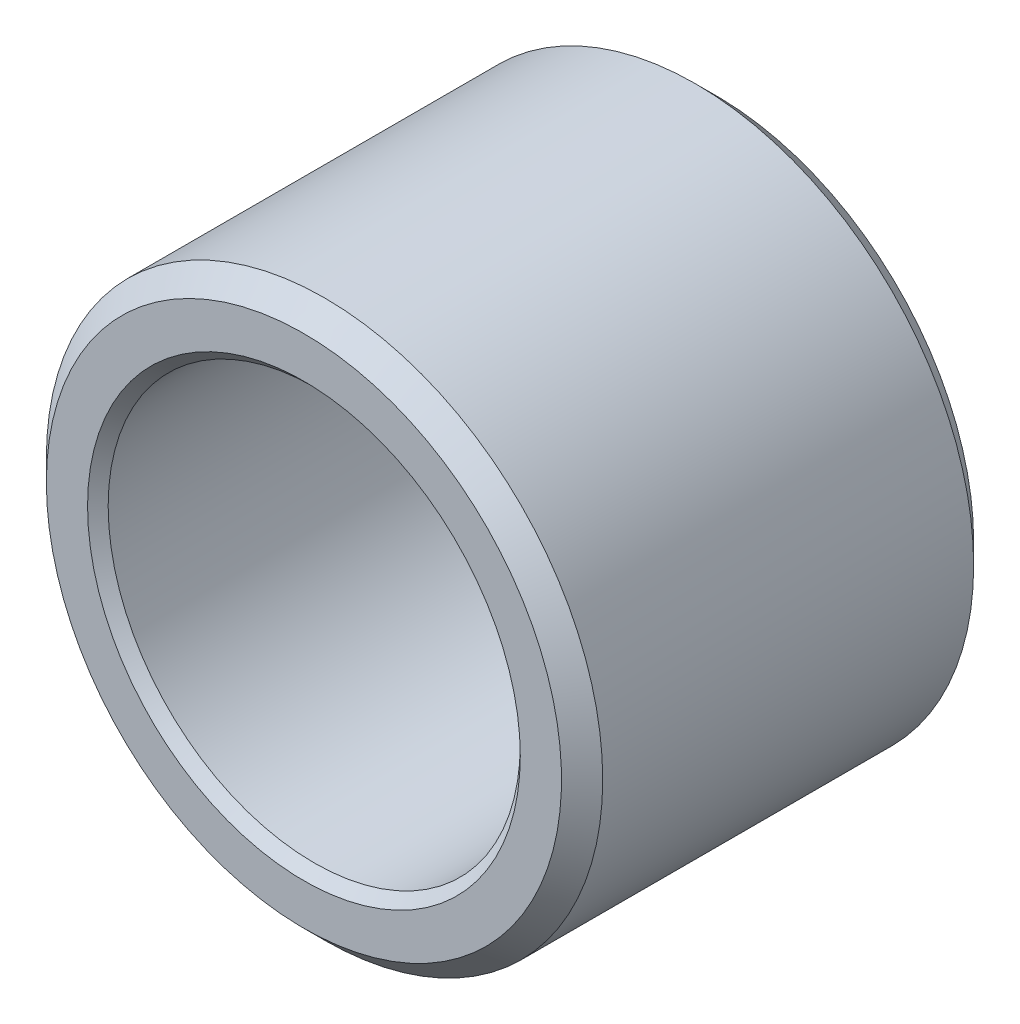
SolidWorks part; units mm, degrees
material "AISI 1045 Acero estirado en frío"
ref_plane "Alzado" through (0, 0, 0) normal (0, 0, 1) x (1, 0, 0)
ref_plane "Planta" through (0, 0, 0) normal (0, 1, 0) x (1, 0, 0)
ref_plane "Vista lateral" through (0, 0, 0) normal (1, 0, 0) x (0, 0, -1)
sketch "Croquis1" plane through (0, 0, 0) normal (0, 0, 1) x (1, 0, 0)
  circle A0 centre (0, 0) radius 13.5
  circle A1 centre (0, 0) radius 10
  dimension "D1" = 27
  dimension "D2" = 20
extrude "Saliente-Extruir1" add sketch "Croquis1" along normal blind 20
chamfer "Chaflán1" distance 1 angle 45 2 edges at (13.5, 0, 20) (13.5, 0, 0)
chamfer "Chaflán2" distance 0.5 angle 45 2 edges at (10, 0, 0) (10, 0, 20)
